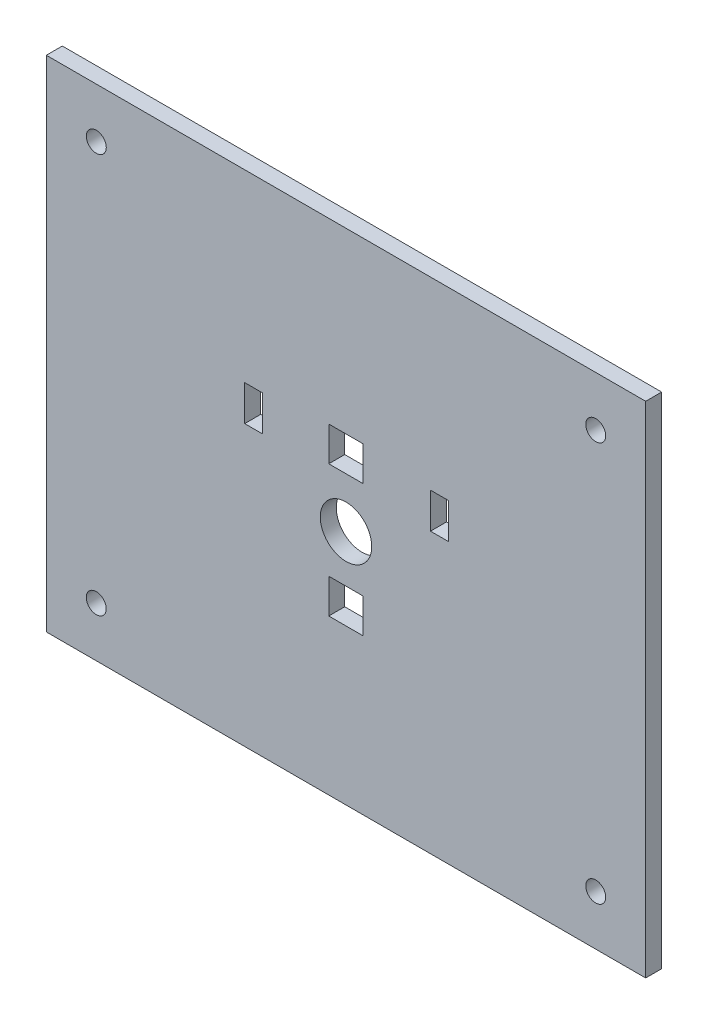
SolidWorks part; units mm, degrees
ref_plane "Front Plane" through (0, 0, 0) normal (0, 0, 1) x (1, 0, 0)
ref_plane "Top Plane" through (0, 0, 0) normal (0, 1, 0) x (1, 0, 0)
ref_plane "Right Plane" through (0, 0, 0) normal (1, 0, 0) x (0, 0, -1)
sketch "Model" plane through (0, 0, 0) normal (0, 0, 1) x (1, 0, 0)
  line L0 (120.461, 77.972) -> (120.461, 81.528)
  line L1 (120.461, 77.972) -> (122.239, 77.972)
  line L2 (122.239, 77.972) -> (122.239, 81.528)
  line L4 (120.461, 81.528) -> (122.239, 81.528)
  line L5 (101.861, 77.997) -> (101.861, 81.553)
  line L6 (103.639, 77.997) -> (103.639, 81.553)
  line L7 (101.861, 81.553) -> (103.639, 81.553)
  line L10 (101.861, 77.997) -> (103.639, 77.997)
  line L12 (110.275, 82.1702) -> (113.725, 82.1702)
  line L13 (113.725, 78.7202) -> (113.725, 82.1702)
  line L14 (110.275, 78.7202) -> (113.725, 78.7202)
  line L15 (110.275, 78.7202) -> (110.275, 82.1702)
  line L16 (110.275, 68.975) -> (113.725, 68.975)
  line L17 (113.725, 65.525) -> (113.725, 68.975)
  line L18 (110.275, 65.525) -> (113.725, 65.525)
  line L19 (110.275, 65.525) -> (110.275, 68.975)
  line L26 (112.0023, 50.0046) -> (112.0023, 100.0046) construction
  line L27 (82.0023, 100.0046) -> (142.0023, 100.0046)
  line L28 (82.0023, 100.0046) -> (82.0023, 50.0046)
  line L29 (82.0023, 50.0046) -> (142.0023, 50.0046)
  line L30 (142.0023, 100.0046) -> (142.0023, 50.0046)
  line L31 (82.0023, 100.0046) -> (142.0023, 50.0046) construction
  line L32 (82.0023, 50.0046) -> (142.0023, 100.0046) construction
  line L33 (142.0023, 75.0046) -> (82.0023, 75.0046) construction
  circle A0 centre (112.0023, 73.6931) radius 2.5757
  circle A3 centre (87.0023, 95.0046) radius 1
  circle A4 centre (137.0023, 95.0046) radius 1
  circle A5 centre (137.0023, 55.0046) radius 1
  circle A6 centre (87.0023, 55.0046) radius 1
  point P3 (111.9691, 61.7296)
  dimension "D1" = 60
  dimension "D5" = 2
  dimension "D2" = 50
  dimension "D6" = 5
  dimension "D7" = 5
extrude "Boss-Extrude1" add sketch "Model" along normal blind 1.6
